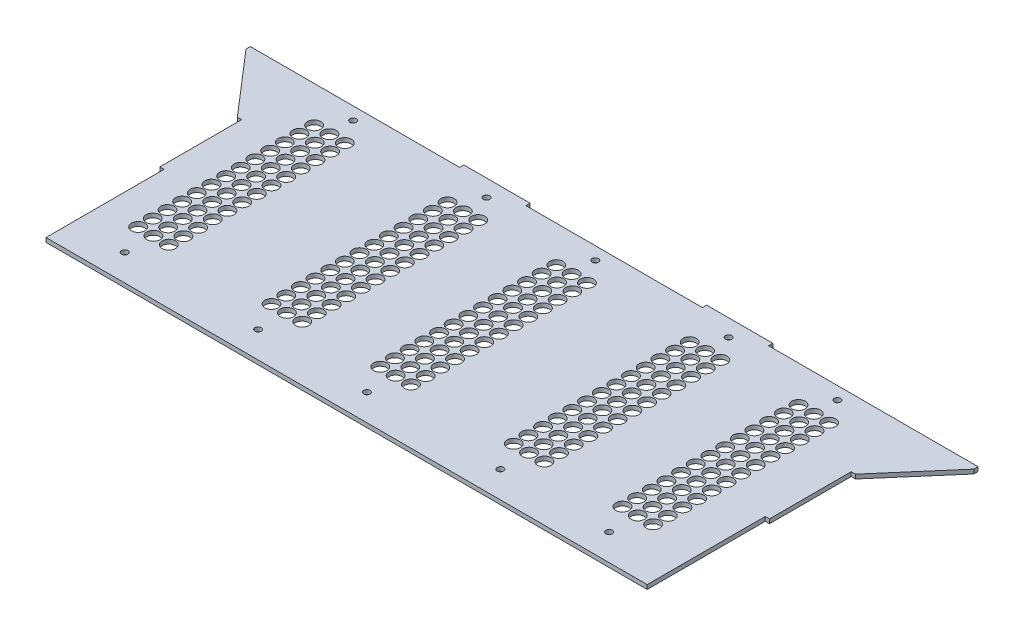
SolidWorks part; units mm, degrees
material "6061-T6 (SS)"
ref_plane "X-Y Datum" through (0, 0, 0) normal (0, 0, 1) x (1, 0, 0)
ref_plane "X-Z Datum" through (0, 0, 0) normal (0, 1, 0) x (1, 0, 0)
ref_plane "Y-Z Datum" through (0, 0, 0) normal (1, 0, 0) x (0, 0, -1)
sketch "Sketch1" plane through (0, 0, 0) normal (0, 0, 1) x (1, 0, 0)
  line L1 (-228.6115, -1.5875) -> (228.6115, -1.5875)
  line L2 (-228.6115, -1.5875) -> (-228.6115, 1.5875)
  line L3 (-228.6115, 1.5875) -> (228.6115, 1.5875)
  line L4 (228.6115, -1.5875) -> (228.6115, 1.5875)
  line L5 (-228.6115, -1.5875) -> (228.6115, 1.5875) construction
  line L6 (-228.6115, 1.5875) -> (228.6115, -1.5875) construction
  point P0 (0, 0)
  dimension "D1" = 3.175
  dimension "D2" = 457.223
extrude "Boss-Extrude1" add sketch "Sketch1" along normal blind 200.642
sketch "Sketch3" plane through (0, 0, 0) normal (0, 0, -1) x (-1, 0, 0)
  line L0 (-66.1907, -1.5583) -> (-66.1907, -1.5875)
  line L9 (228.6115, -1.5875) -> (-228.6115, -1.5875) construction
  line L11 (-228.6115, 1.5875) -> (228.6115, 1.5875) construction
  line L12 (-228.6115, 1.5875) -> (228.6115, 1.5875) construction
  line L13 (-66.1907, -1.5875) -> (-115.8495, -1.5875)
  line L14 (-66.1907, -1.5875) -> (-66.1907, 1.5875)
  line L15 (-66.1907, 1.5875) -> (-115.8495, 1.5875)
  line L16 (-115.8495, -1.5875) -> (-115.8495, 1.5875)
  line L17 (66.1907, -1.5875) -> (115.8495, -1.5875)
  line L18 (66.1907, -1.5875) -> (66.1907, 1.5875)
  line L19 (66.1907, 1.5875) -> (115.8495, 1.5875)
  line L20 (115.8495, -1.5875) -> (115.8495, 1.5875)
  dimension "D2" = 49.6588
sketch "Sketch4" plane through (0, -1.5875, 0) normal (0, -1, 0) x (1, 0, 0)
  line L0 (-228.6115, 0) -> (-272.8865, 0)
  line L2 (-228.6115, 200.642) -> (-228.6115, 0) construction
  line L3 (-228.6115, 50.8) -> (-228.6115, 0)
  line L4 (-272.8865, 0) -> (-272.8865, 3.175)
  line L6 (-228.6115, 50.8) -> (-231.7865, 50.8)
  line L7 (-272.8865, 3.175) -> (-231.7865, 50.8)
  dimension "D1" = 44.275
  dimension "D2" = 50.8
  dimension "D3" = 3.175
  dimension "D4" = 3.175
extrude "Boss-Extrude3" add sketch "Sketch4" against normal blind 3.175
mirror "Mirror1" about plane through (0, 0, 0) normal (1, 0, 0) of "Boss-Extrude3"
sketch "Sketch5" plane through (0, -1.5875, 0) normal (0, -1, 0) x (1, 0, 0)
  line L1 (-228.6115, 200.642) -> (-225.4365, 200.642)
  line L2 (-228.6115, 200.642) -> (-228.6115, 112.128)
  line L3 (-228.6115, 112.128) -> (-225.4365, 112.128)
  line L4 (-225.4365, 200.642) -> (-225.4365, 112.128)
  dimension "D1" = 3.175
  dimension "D2" = 88.514
extrude "Cut-Extrude2" cut sketch "Sketch5" against normal blind 3.175
mirror "Mirror2" about plane through (0, 0, 0) normal (1, 0, 0) of "Cut-Extrude2"
extrude "Boss-Extrude4" add sketch "Sketch3" along normal blind 3.18
sketch "Sketch6" plane through (0, -1.5875, 0) normal (0, -1, 0) x (1, 0, 0)
  point P0 (-186.2355, 9.525)
  point P1 (-186.2355, 180.775)
hole_wizard "M4 Clearance Hole1" positions "Sketch6" profile "Sketch7" hole size "M4" standard "ANSI Metric" end condition through all
sketch "Sketch7" plane through (-186.2355, -1.5875, 9.525) normal (1, 0, 0) x (0, 0, -1)
  line L0 (0, 0) -> (0, 3.175)
  line L1 (0, 3.175) -> (2.4, 3.175)
  line L2 (2.4, 3.175) -> (2.4, 0)
  line L5 (2.4, 0) -> (0, 0)
  line L11 (0, -6.35) -> (0, 107.95) construction
  dimension "Thru Hole Dia." = 4.8
  dimension "Thru Hole Depth" = 3.175
pattern_linear "LPattern5" count 3 spacing 181.614 along (1, 0, 0) of "M4 Clearance Hole1"
sketch "Sketch8" plane through (0, -1.5875, 0) normal (0, -1, 0) x (1, 0, 0)
  point P0 (-86.1905, 9.525)
  point P1 (-86.1905, 180.775)
hole_wizard "M4 Clearance Hole2" positions "Sketch8" profile "Sketch9" hole size "M4" standard "ANSI Metric" end condition through all
sketch "Sketch9" plane through (-86.1905, -1.5875, 9.525) normal (1, 0, 0) x (0, 0, -1)
  line L0 (0, 0) -> (0, 3.175)
  line L1 (0, 3.175) -> (2.4, 3.175)
  line L2 (2.4, 3.175) -> (2.4, 0)
  line L5 (2.4, 0) -> (0, 0)
  line L11 (0, -6.35) -> (0, 107.95) construction
  dimension "Thru Hole Dia." = 4.8
  dimension "Thru Hole Depth" = 3.175
pattern_linear "LPattern6" count 2 spacing 181.614 along (1, 0, 0) of "M4 Clearance Hole2"
sketch "Sketch10" plane through (0, -1.5875, 0) normal (0, -1, 0) x (1, 0, 0)
  circle A0 centre (-174.7355, 159.2567) radius 5 construction
  circle A1 centre (-186.2355, 159.2567) radius 5 construction
  circle A2 centre (-197.7355, 159.2567) radius 5 construction
  circle A3 centre (-174.7355, 159.2567) radius 5
  circle A4 centre (-186.2355, 159.2567) radius 5
  circle A5 centre (-197.7355, 159.2567) radius 5
  circle A6 centre (-74.6905, 159.2567) radius 5 construction
  circle A7 centre (-86.1905, 159.2567) radius 5 construction
  circle A8 centre (-97.6905, 159.2567) radius 5 construction
  circle A9 centre (-74.6905, 159.2567) radius 5
  circle A10 centre (-86.1905, 159.2567) radius 5
  circle A11 centre (-97.6905, 159.2567) radius 5
extrude "Cut-Extrude3" cut sketch "Sketch10" against normal through all contours A5 | A4 | A3
pattern_linear "LPattern1" count 13 spacing 11 along (0, 0, -1) of "Cut-Extrude3"
pattern_linear "LPattern2" count 3 spacing 181.614 along (1, 0, 0) of "Cut-Extrude3", "LPattern1"
sketch "Sketch11" plane through (0, -1.5875, 0) normal (0, -1, 0) x (1, 0, 0)
  circle A1 centre (-74.6905, 159.2567) radius 5
  circle A2 centre (-74.6905, 159.2567) radius 5
  circle A3 centre (-197.7355, 159.2567) radius 5
  circle A4 centre (-197.7355, 159.2567) radius 5
  circle A5 centre (-186.2355, 159.2567) radius 5
  circle A6 centre (-186.2355, 159.2567) radius 5
  circle A7 centre (-174.7355, 159.2567) radius 5
  circle A8 centre (-174.7355, 159.2567) radius 5
  circle A9 centre (-97.6905, 159.2567) radius 5
  circle A10 centre (-97.6905, 159.2567) radius 5
  circle A11 centre (-86.1905, 159.2567) radius 5
  circle A12 centre (-86.1905, 159.2567) radius 5
  dimension "D1" = 0
  dimension "D2" = 0
  dimension "D3" = 0
  dimension "D4" = 0
  dimension "D5" = 0
  dimension "D6" = 0
extrude "Cut-Extrude4" cut sketch "Sketch11" against normal through all contours A10 | A12 | A2
pattern_linear "LPattern3" count 13 spacing 11 along (0, 0, -1) of "Cut-Extrude4"
pattern_linear "LPattern4" count 2 spacing 181.614 along (1, 0, 0) of "LPattern3", "Cut-Extrude4"
